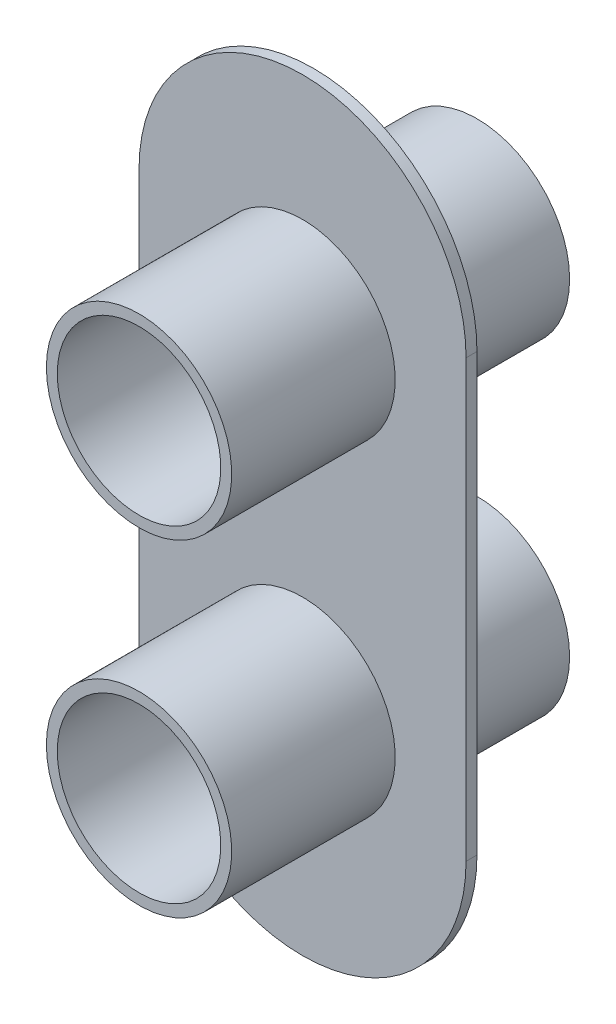
SolidWorks part; units mm, degrees
material "Custom Plastic"
ref_plane "X-Y Datum" through (0, 0, 0) normal (0, 0, 1) x (1, 0, 0)
ref_plane "X-Z Datum" through (0, 0, 0) normal (0, 1, 0) x (1, 0, 0)
ref_plane "Y-Z Datum" through (0, 0, 0) normal (1, 0, 0) x (0, 0, -1)
sketch "Sketch1" plane through (0, 0, 0) normal (0, 0, 1) x (1, 0, 0)
  line L1 (0, -43.0151) -> (0, 43.0151) construction
  line L2 (0, 50.8) -> (-38.1, 50.8)
  line L3 (-38.1, 50.8) -> (-38.1, -50.8)
  line L4 (-38.1, -50.8) -> (0, -50.8)
  line L5 (0, -50.8) -> (38.1, -50.8)
  line L6 (38.1, -50.8) -> (38.1, 50.8)
  line L7 (38.1, 50.8) -> (0, 50.8)
  circle A0 centre (0, 50.8) radius 38.1
  circle A1 centre (0, -50.8) radius 38.1
  dimension "D1" = 101.6
extrude "Boss-Extrude1" add sketch "Sketch1" along normal blind 2.54 contours L7 A0 L2 | A1 L6 A0 L3 | L4 A1 L5 | L5 A1 L4 | L2 A0 L7
sketch "Sketch2" plane through (0, 0, 2.54) normal (0, 0, 1) x (1, 0, 0)
  line L0 (0, -38.1) -> (0, 38.1)
  line L1 (-24.7906, 0) -> (24.7906, 0)
  circle A0 centre (0, 38.1) radius 21.59
  circle A1 centre (0, -38.1) radius 21.59
  point P7 (0, 0)
  point P8 (0, 0)
  dimension "D1" = 38.1
  dimension "D2" = 43.18
sketch "Sketch5" plane through (0, 0, 0) normal (0, 0, -1) x (-1, 0, 0)
  line L0 (0, 38.1) -> (0, -38.1)
  line L1 (-24.7906, 0) -> (24.7906, 0)
  circle A0 centre (0, 38.1) radius 21.59
  circle A1 centre (0, -38.1) radius 21.59
  point P8 (0, 0)
  point P10 (0, 0)
  dimension "D1" = 43.18
extrude "Boss-Extrude5" add sketch "Sketch5" along normal blind 38.1 contours A1 | A0
extrude "Boss-Extrude6" add sketch "Sketch2" along normal blind 38.1 contours A1 | A0
sketch "Sketch6" plane through (0, 0, -38.1) normal (0, 0, -1) x (-1, 0, 0)
  circle A0 centre (0, 38.1) radius 19.05
  circle A1 centre (0, -38.1) radius 19.05
extrude "Cut-Extrude2" cut sketch "Sketch6" against normal through all both and the other way through all
